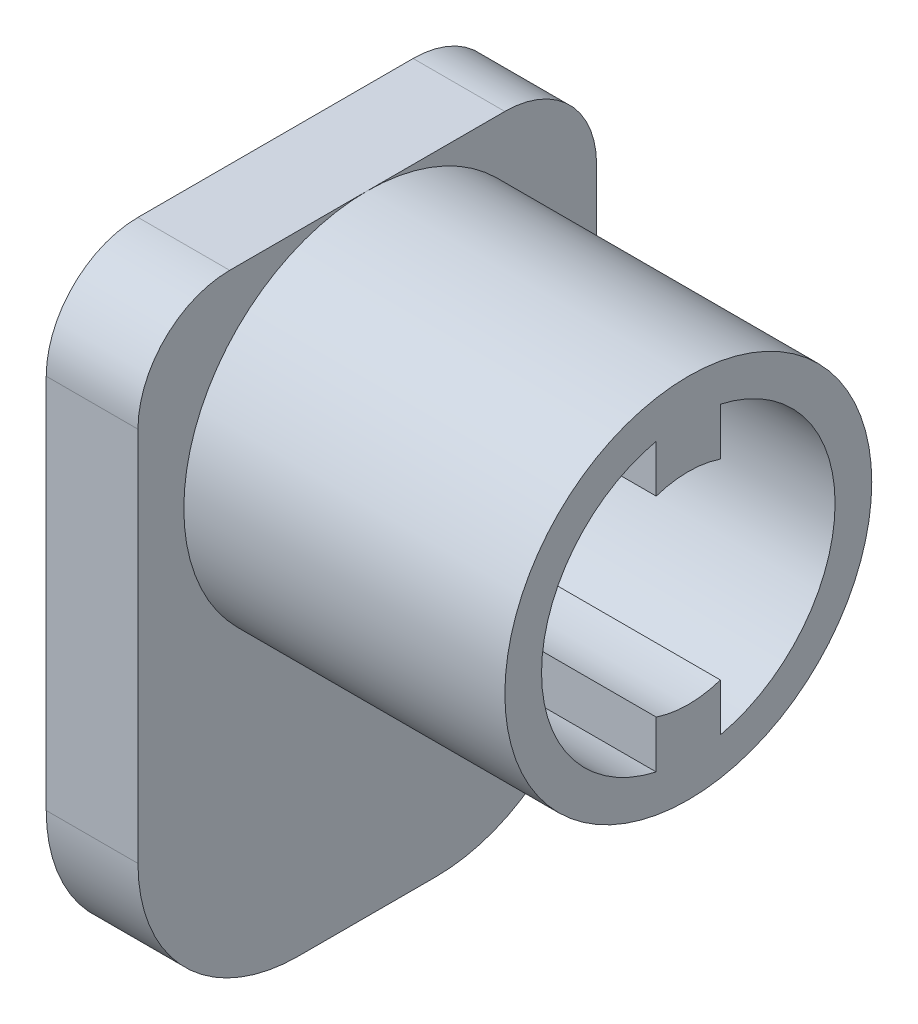
SolidWorks part; units mm, degrees
ref_plane "Front Plane" through (0, 0, 0) normal (0, 0, 1) x (1, 0, 0)
ref_plane "Top Plane" through (0, 0, 0) normal (0, 1, 0) x (1, 0, 0)
ref_plane "Right Plane" through (0, 0, 0) normal (1, 0, 0) x (0, 0, -1)
sketch "Sketch2" plane through (0, 0, 0) normal (1, 0, 0) x (0, 0, -1)
  circle A0 centre (0, 0) radius 4
  dimension "D1" = 8
extrude "Boss-Extrude1" add sketch "Sketch2" against normal blind 7
sketch "Sketch3" plane through (-7, 0, 0) normal (-1, 0, 0) x (0, 0, 1)
  line L0 (0, 0) -> (0, -9.7) construction
  line L1 (-5, 4) -> (5, 4)
  line L2 (-5, 4) -> (-5, -9.7)
  line L3 (-5, -9.7) -> (5, -9.7)
  line L4 (5, 4) -> (5, -9.7)
  dimension "D1" = 9.7
  dimension "D2" = 4
  dimension "D3" = 10
extrude "Boss-Extrude2" add sketch "Sketch3" along normal blind 2
sketch "Sketch4" plane through (0, 0, 0) normal (1, 0, 0) x (0, 0, -1)
  circle A0 centre (0, 0) radius 3.2
  dimension "D1" = 6.4
extrude "Cut-Extrude1" cut sketch "Sketch4" against normal up to surface (7 mm away) up to face at (-7, -1.2333, -0.6667)
sketch "Sketch6" plane through (-9, 0, 0) normal (-1, 0, 0) x (0, 0, 1)
  line L6 (0.7, -2.8618) -> (0.7, -1.7861)
  line L7 (0.7, -2.8618) -> (0.7, -2.0857)
  line L8 (-0.7, -2.8618) -> (0.7, -2.8618) construction
  line L9 (-0.7, -1.7861) -> (-0.7, -2.8618)
  line L10 (-0.7, -2.0857) -> (-0.7, -2.8618)
  line L12 (0, 0) -> (5, 0) construction
  line L13 (5, -9.7) -> (5, 4) construction
  line L15 (-0.7, 2.0857) -> (-0.7, 2.8618)
  line L16 (-0.7, 2.8618) -> (0.7, 2.8618) construction
  line L17 (0.7, 2.8618) -> (0.7, 2.0857)
  line L18 (-0.7, -2.8618) -> (-0.7, -3.1225)
  line L19 (0.7, -2.8618) -> (0.7, -3.1225)
  line L20 (-0.7, 2.8618) -> (-0.7, 3.1225)
  line L21 (0.7, 2.8618) -> (0.7, 3.1225)
  arc A1 (-0.7, 2.0857) -> (0.7, 2.0857) centre (0, 0) cw
  arc A2 (-0.99, -1.9647) -> (0.99, -1.9647) centre (0, 0) ccw
  arc A3 (-0.7, -2.0857) -> (0.7, -2.0857) centre (0, 0) ccw
  circle A4 centre (0, 0) radius 3.2 construction
  arc A5 (-0.7, -3.1225) -> (0.7, -3.1225) centre (0, 0) ccw
  arc A6 (-0.7, 3.1225) -> (0.7, 3.1225) centre (0, 0) cw
  dimension "D3" = 0.2
  dimension "D1" = 0.2
  dimension "D2" = 0.2
sketch "Sketch7" plane through (-9, 0, 0) normal (-1, 0, 0) x (0, 0, 1)
  circle A0 centre (0, 0) radius 1.6
  dimension "D1" = 3.2
extrude "Cut-Extrude4" cut sketch "Sketch7" against normal through all
extrude "Boss-Extrude3" add sketch "Sketch6" against normal up to surface (9 mm away) up to face at (0, 0, -3.2)
fillet "Fillet2" radius 2 2 edges at (-8, 4, 5) (-8, 4, -5)
fillet "Fillet3" radius 3.5 2 edges at (-8, -9.7, -5) (-8, -9.7, 5)
